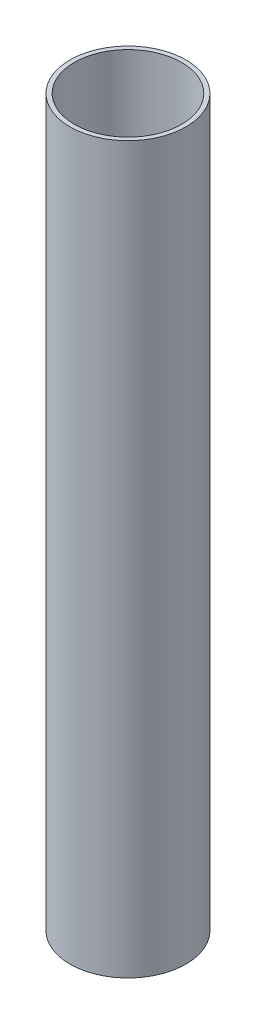
SolidWorks part; units mm, degrees
ref_plane "Front Plane" through (0, 0, 0) normal (0, 0, 1) x (1, 0, 0)
ref_plane "Top Plane" through (0, 0, 0) normal (0, 1, 0) x (1, 0, 0)
ref_plane "Right Plane" through (0, 0, 0) normal (1, 0, 0) x (0, 0, -1)
sketch "Sketch1" plane through (0, 0, 0) normal (0, 1, 0) x (1, 0, 0)
  circle A0 centre (0, 0) radius 16
  circle A1 centre (0, 0) radius 14.8
  dimension "D1" = 1.2
  dimension "D2" = 32
extrude "Boss-Extrude1" add sketch "Sketch1" along normal blind 200
